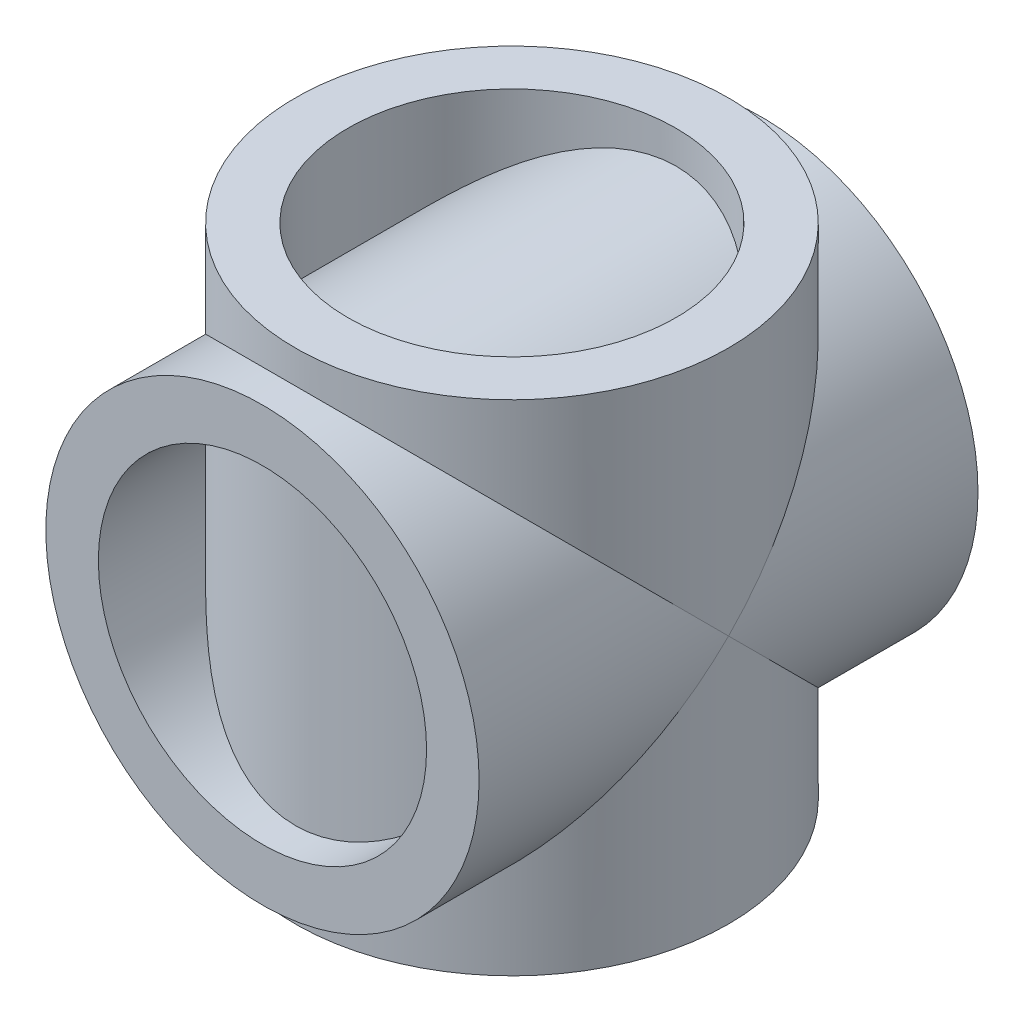
SolidWorks part; units mm, degrees
ref_plane "Front Plane" through (0, 0, 0) normal (0, 0, 1) x (1, 0, 0)
ref_plane "Top Plane" through (0, 0, 0) normal (0, 1, 0) x (1, 0, 0)
ref_plane "Right Plane" through (0, 0, 0) normal (1, 0, 0) x (0, 0, -1)
sketch "Sketch2" plane through (0, 0, 0) normal (0, 0, 1) x (1, 0, 0)
  circle A0 centre (0, 0) radius 6.25
  dimension "D1" = 12.5
extrude "Extrude-Thin1" add sketch "Sketch2" along normal blind 19 thin
sketch "Sketch4" plane through (0, 0, 0) normal (0, 1, 0) x (1, 0, 0)
  line L0 (0, 0) -> (0, -19) construction
  line L1 (-8.25, -19) -> (8.25, -19) construction
  line L2 (-8.25, -9.5) -> (8.25, -9.5) construction
  line L3 (-8.25, 0) -> (-8.25, -19) construction
  line L4 (8.25, -19) -> (8.25, 0) construction
  circle A0 centre (0, -9.5) radius 6.25
  dimension "D1" = 12.5
extrude "Extrude-Thin2" add sketch "Sketch4" along normal mid plane 19 thin
